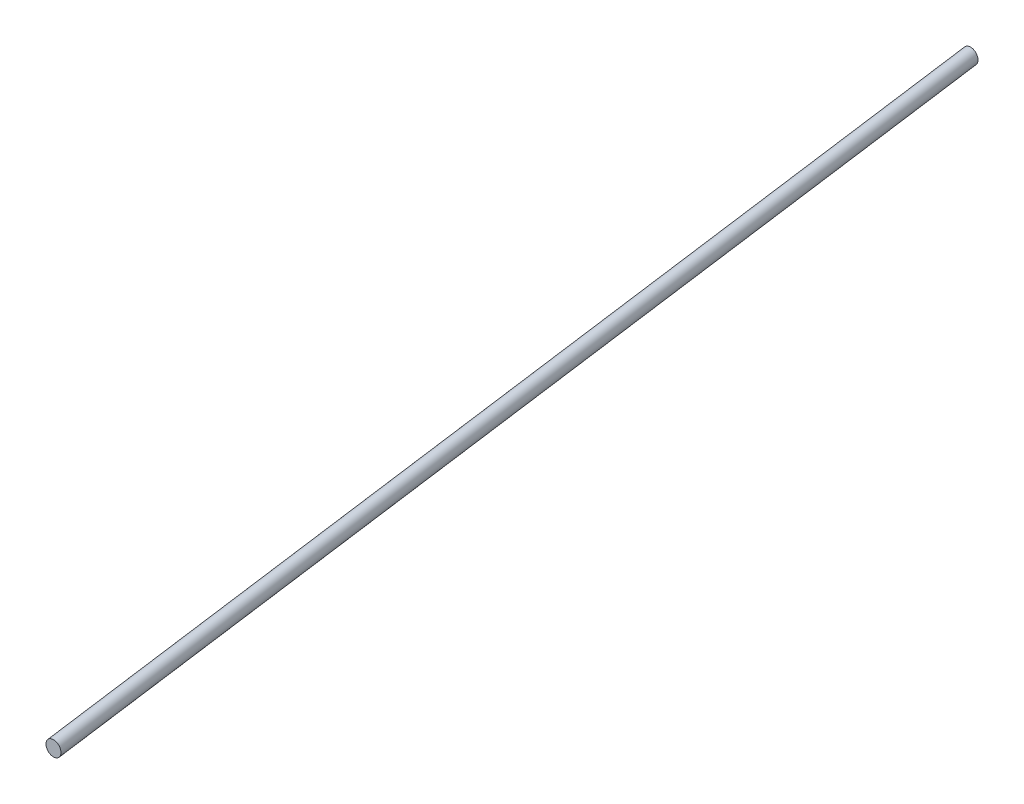
SolidWorks part; units mm, degrees
material "Hexcel AS4C (3000 丝)"
ref_plane "前视基准面" through (0, 0, 0) normal (0, 0, 1) x (1, 0, 0)
ref_plane "上视基准面" through (0, 0, 0) normal (0, 1, 0) x (1, 0, 0)
ref_plane "右视基准面" through (0, 0, 0) normal (1, 0, 0) x (0, 0, -1)
curve "曲线1"
  spline degree 3 poles (186.5, 0.1118, 0) (186.1892, 0.1855, 0) (185.5675, 0.3328, 0) (184.635, 0.5537, 0) (183.7026, 0.7744, 0) (182.7701, 0.9948, 0) (181.8376, 1.2145, 0) (180.9051, 1.4337, 0) (179.9726, 1.652, 0) (178.7297, 1.9419, 0) (177.1757, 2.3014, 0) (175.3109, 2.728, 0) (173.4457, 3.1494, 0) (171.5809, 3.5657, 0) (169.7157, 3.9772, 0) (167.8508, 4.3838, 0) (165.9856, 4.7859, 0) (164.1208, 5.1833, 0) (162.2556, 5.576, 0) (160.3908, 5.9638, 0) (158.5257, 6.3468, 0) (156.6608, 6.7247, 0) (154.7957, 7.0976, 0) (152.9308, 7.4653, 0) (151.0657, 7.8278, 0) (149.2008, 8.185, 0) (147.3357, 8.5369, 0) (145.4708, 8.8834, 0) (143.6056, 9.2245, 0) (141.7408, 9.5601, 0) (139.8756, 9.8903, 0) (138.0108, 10.2149, 0) (136.1456, 10.5341, 0) (134.2808, 10.8476, 0) (132.4156, 11.1557, 0) (130.5507, 11.4581, 0) (128.6856, 11.7549, 0) (126.8208, 12.0459, 0) (124.9556, 12.3308, 0) (123.0908, 12.6092, 0) (121.2257, 12.8811, 0) (119.3608, 13.146, 0) (117.4957, 13.4038, 0) (115.6308, 13.654, 0) (113.7657, 13.8966, 0) (111.9008, 14.1311, 0) (110.0357, 14.3574, 0) (108.1708, 14.5754, 0) (106.3056, 14.785, 0) (104.4407, 14.9862, 0) (102.5756, 15.1791, 0) (100.7107, 15.3636, 0) (98.8455, 15.5397, 0) (96.9806, 15.7073, 0) (95.1155, 15.8666, 0) (93.2506, 16.0175, 0) (91.3854, 16.1599, 0) (89.5205, 16.2936, 0) (87.6554, 16.4183, 0) (85.7905, 16.5335, 0) (83.9254, 16.6389, 0) (82.0604, 16.734, 0) (80.1953, 16.8187, 0) (78.3303, 16.8924, 0) (76.4652, 16.9548, 0) (74.6002, 17.0055, 0) (72.7351, 17.0439, 0) (70.8701, 17.0706, 0) (69.005, 17.0858, 0) (67.14, 17.0901, 0) (65.275, 17.0839, 0) (63.4099, 17.0678, 0) (61.5449, 17.0422, 0) (59.6799, 17.0076, 0) (57.8149, 16.9643, 0) (55.9498, 16.9131, 0) (54.0848, 16.8547, 0) (52.2196, 16.7871, 0) (50.3546, 16.7086, 0) (48.4893, 16.6167, 0) (46.6243, 16.5092, 0) (44.7588, 16.3837, 0) (42.8937, 16.238, 0) (41.028, 16.0697, 0) (39.163, 15.8765, 0) (37.2969, 15.6558, 0) (35.4322, 15.405, 0) (33.5661, 15.1238, 0) (31.7016, 14.8124, 0) (29.8355, 14.4709, 0) (27.971, 14.1006, 0) (26.1044, 13.6997, 0) (24.2398, 13.2683, 0) (22.3723, 12.8019, 0) (20.5078, 12.299, 0) (18.6397, 11.7536, 0) (16.7761, 11.1641, 0) (14.9067, 10.5272, 0) (13.0406, 9.8463, 0) (11.4871, 9.2257, 0) (10.251, 8.6897, 0) (9.3149, 8.2577, 0) (8.3827, 7.7965, 0) (7.4442, 7.2957, 0) (6.5109, 6.7553, 0) (5.5667, 6.1517, 0) (4.6345, 5.4819, 0) (3.7611, 4.7729, 0) (2.9674, 4.0489, 0) (2.3522, 3.4464, 0) (1.8596, 2.9514, 0) (1.4788, 2.552, 0) (1.1014, 2.1276, 0) (0.7887, 1.7312, 0) (0.5474, 1.381, 0) (0.3916, 1.1217, 0) (0.2725, 0.8921, 0) (0.1949, 0.7195, 0) (0.136, 0.5671, 0) (0.0831, 0.4095, 0) (0.0327, 0.2211, 0) (-0.0162, -0.071, 0) (-0.0149, -0.4421, 0) (0.0563, -0.7734, 0) (0.1356, -0.9912, 0) (0.1948, -1.1301, 0) (0.2723, -1.2864, 0) (0.3907, -1.4912, 0) (0.546, -1.7187, 0) (0.7851, -2.0147, 0) (1.0965, -2.3364, 0) (1.4716, -2.656, 0) (1.8524, -2.9339, 0) (2.3365, -3.2337, 0) (2.9612, -3.5284, 0) (3.7741, -3.807, 0) (4.6559, -4.0277, 0) (5.5923, -4.2156, 0) (6.5261, -4.402, 0) (7.4574, -4.5763, 0) (8.3903, -4.7294, 0) (9.3228, -4.8608, 0) (10.2562, -4.9705, 0) (11.4987, -5.092, 0) (13.0535, -5.2066, 0) (14.9192, -5.3092, 0) (16.7846, -5.4024, 0) (18.6495, -5.482, 0) (20.5147, -5.5442, 0) (22.3797, -5.5905, 0) (24.2449, -5.6228, 0) (26.1099, -5.6419, 0) (27.975, -5.6487, 0) (29.84, -5.6442, 0) (31.7051, -5.6295, 0) (33.5701, -5.6055, 0) (35.4351, -5.5733, 0) (37.3001, -5.5337, 0) (39.1651, -5.4878, 0) (41.0301, -5.4363, 0) (42.8951, -5.3798, 0) (44.7601, -5.3192, 0) (46.6251, -5.2551, 0) (48.4901, -5.1881, 0) (50.355, -5.1191, 0) (52.22, -5.0486, 0) (54.085, -4.9774, 0) (55.95, -4.9063, 0) (57.815, -4.8359, 0) (59.68, -4.7662, 0) (61.545, -4.6971, 0) (63.41, -4.6284, 0) (65.275, -4.5602, 0) (67.14, -4.4922, 0) (69.005, -4.4244, 0) (70.87, -4.3567, 0) (72.735, -4.2891, 0) (74.6, -4.2213, 0) (76.465, -4.1533, 0) (78.33, -4.0852, 0) (80.195, -4.0168, 0) (82.06, -3.9484, 0) (83.925, -3.8798, 0) (85.79, -3.8112, 0) (87.655, -3.7425, 0) (89.52, -3.6738, 0) (91.385, -3.6051, 0) (93.25, -3.5364, 0) (95.115, -3.4678, 0) (96.98, -3.3992, 0) (98.845, -3.3306, 0) (100.71, -3.2621, 0) (102.575, -3.1937, 0) (104.44, -3.1252, 0) (106.305, -3.0568, 0) (108.17, -2.9883, 0) (110.035, -2.9199, 0) (111.9, -2.8515, 0) (113.765, -2.783, 0) (115.63, -2.7145, 0) (117.495, -2.6461, 0) (119.36, -2.5776, 0) (121.225, -2.5091, 0) (123.09, -2.4406, 0) (124.955, -2.3721, 0) (126.82, -2.3035, 0) (128.685, -2.2351, 0) (130.55, -2.1665, 0) (132.415, -2.0981, 0) (134.28, -2.0295, 0) (136.145, -1.9611, 0) (138.01, -1.8926, 0) (139.875, -1.8241, 0) (141.74, -1.7556, 0) (143.605, -1.6871, 0) (145.47, -1.6186, 0) (147.335, -1.5501, 0) (149.2, -1.4816, 0) (151.065, -1.4131, 0) (152.93, -1.3446, 0) (154.795, -1.2761, 0) (156.66, -1.2076, 0) (158.525, -1.1392, 0) (160.39, -1.0707, 0) (162.255, -1.0022, 0) (164.12, -0.9337, 0) (165.985, -0.8652, 0) (167.85, -0.7967, 0) (169.715, -0.7282, 0) (171.58, -0.6597, 0) (173.445, -0.5912, 0) (175.31, -0.5227, 0) (177.175, -0.4542, 0) (178.7292, -0.3972, 0) (179.9725, -0.3515, 0) (180.905, -0.3173, 0) (181.8375, -0.283, 0) (182.77, -0.2488, 0) (183.7025, -0.2145, 0) (184.635, -0.1803, 0) (185.5675, -0.146, 0) (186.1892, -0.1232, 0) (186.5, -0.1118, 0) knots 0 0 0 0 0.002514 0.005028 0.007541 0.010055 0.012567 0.01508 0.017592 0.020104 0.025124 0.030144 0.035158 0.040172 0.04518 0.050189 0.055192 0.060195 0.065193 0.070191 0.075184 0.080177 0.085164 0.090152 0.095134 0.100117 0.105094 0.110071 0.115043 0.120015 0.124982 0.129949 0.134911 0.139873 0.14483 0.149787 0.154739 0.159692 0.164639 0.169587 0.174529 0.179472 0.184409 0.189346 0.194278 0.19921 0.204137 0.209064 0.213985 0.218907 0.223824 0.228741 0.233654 0.238567 0.243476 0.248385 0.25329 0.258196 0.263098 0.268 0.2729 0.277799 0.282695 0.287592 0.292486 0.29738 0.302273 0.307166 0.312058 0.316951 0.321843 0.326735 0.331628 0.33652 0.341414 0.346308 0.351203 0.356098 0.360995 0.365892 0.370794 0.375696 0.380605 0.385515 0.390437 0.39536 0.400301 0.405243 0.410209 0.415176 0.420172 0.425167 0.430199 0.435232 0.440314 0.445396 0.450545 0.455694 0.460935 0.466175 0.468856 0.471537 0.474288 0.477039 0.479906 0.482773 0.485854 0.488934 0.491619 0.494305 0.49571 0.497115 0.498647 0.500178 0.501085 0.501992 0.502556 0.503119 0.50348 0.503841 0.504427 0.505013 0.506168 0.507324 0.507658 0.507992 0.508511 0.50903 0.509853 0.510676 0.512022 0.513369 0.514549 0.515728 0.517845 0.519968 0.522481 0.524993 0.527484 0.529974 0.532448 0.534923 0.537383 0.539844 0.544747 0.54965 0.554547 0.559445 0.564339 0.569233 0.574126 0.579018 0.58391 0.588803 0.593695 0.598587 0.60348 0.608373 0.613267 0.618161 0.623055 0.62795 0.632845 0.63774 0.642636 0.647531 0.652427 0.657322 0.662218 0.667113 0.672009 0.676904 0.6818 0.686695 0.69159 0.696486 0.701381 0.706276 0.711172 0.716067 0.720962 0.725858 0.730753 0.735649 0.740544 0.745439 0.750335 0.75523 0.760126 0.765021 0.769916 0.774812 0.779707 0.784603 0.789498 0.794393 0.799289 0.804184 0.80908 0.813975 0.81887 0.823766 0.828661 0.833557 0.838452 0.843347 0.848243 0.853138 0.858034 0.862929 0.867824 0.87272 0.877615 0.882511 0.887406 0.892301 0.897197 0.902092 0.906987 0.911883 0.916778 0.921674 0.926569 0.931464 0.93636 0.941255 0.946151 0.951046 0.955941 0.960837 0.965732 0.970628 0.975523 0.980418 0.982866 0.985314 0.987762 0.990209 0.992657 0.995105 0.997552 1 1 1 1
sketch "草图1" plane through (0, 0, 0) normal (0, 0, 1) x (1, 0, 0)
  line L0 (186.5, 0.1118) -> (187.3165, -0.0818)
  line L1 (186.5, -0.1118) -> (187.3165, -0.0818)
  spline S0 degree 3 poles (1071.8943, 1773.6481) (478.7543, -73.3687) (332.3255, -34.4387) (184.635, 0.5537) (183.7026, 0.7744) (182.7701, 0.9948) (181.8376, 1.2145) (180.9051, 1.4337) (179.9726, 1.652) (178.7297, 1.9419) (177.1757, 2.3014) (175.3109, 2.728) (173.4457, 3.1494) (170.9597, 3.7043) (167.8519, 4.3859) (164.1219, 5.1854) (159.7716, 6.0959) (156.0406, 6.8521) (152.9308, 7.4653) (151.0657, 7.8278) (149.2008, 8.185) (147.3357, 8.5369) (145.4708, 8.8834) (143.6056, 9.2245) (141.7408, 9.5601) (139.2547, 10.0002) (136.7681, 10.4294) (134.2808, 10.8476) (132.4156, 11.1557) (130.5507, 11.4581) (128.6856, 11.7549) (126.8208, 12.0459) (124.9556, 12.3308) (123.0908, 12.6092) (121.2257, 12.8811) (119.3608, 13.146) (117.4957, 13.4038) (115.0097, 13.7374) (112.523, 14.0557) (109.4148, 14.4328) (106.9281, 14.7178) (104.4407, 14.9862) (102.5756, 15.1791) (100.7107, 15.3636) (98.8455, 15.5397) (96.3593, 15.7632) (93.2513, 16.0216) (90.1425, 16.252) (87.6554, 16.4183) (85.7905, 16.5335) (83.9254, 16.6389) (82.0604, 16.734) (80.1953, 16.8187) (78.3303, 16.8924) (76.4652, 16.9548) (73.9787, 17.0223) (71.4919, 17.0655) (69.005, 17.0858) (67.14, 17.0901) (65.275, 17.0839) (63.4099, 17.0678) (61.5449, 17.0422) (59.6799, 17.0076) (57.8149, 16.9643) (55.9498, 16.9131) (54.0848, 16.8547) (52.2196, 16.7871) (50.3546, 16.7086) (48.4893, 16.6167) (46.6243, 16.5092) (44.7588, 16.3837) (42.8937, 16.238) (41.028, 16.0697) (39.163, 15.8765) (37.2969, 15.6558) (35.4322, 15.405) (33.5661, 15.1238) (31.7016, 14.8124) (29.8355, 14.4709) (27.971, 14.1006) (26.1044, 13.6997) (24.2398, 13.2683) (22.3723, 12.8019) (20.5078, 12.299) (18.6397, 11.7536) (16.7761, 11.1641) (14.9067, 10.5272) (13.0406, 9.8463) (11.4871, 9.2257) (10.251, 8.6897) (9.3149, 8.2577) (8.3827, 7.7965) (7.4442, 7.2957) (6.5109, 6.7553) (5.5667, 6.1517) (4.6345, 5.4819) (3.7611, 4.7729) (2.9674, 4.0489) (2.3522, 3.4464) (1.8596, 2.9514) (1.4788, 2.552) (1.1014, 2.1276) (0.7887, 1.7312) (0.5474, 1.381) (0.3916, 1.1217) (0.2725, 0.8921) (0.1949, 0.7195) (0.136, 0.5671) (0.0831, 0.4095) (0.0327, 0.2211) (-0.0162, -0.071) (-0.0149, -0.4421) (0.0563, -0.7734) (0.1356, -0.9912) (0.1948, -1.1301) (0.2723, -1.2864) (0.3907, -1.4912) (0.546, -1.7187) (0.7851, -2.0147) (1.0965, -2.3364) (1.4716, -2.656) (1.8524, -2.9339) (2.3365, -3.2337) (2.9612, -3.5284) (3.7741, -3.807) (4.6559, -4.0277) (5.5923, -4.2156) (6.5261, -4.402) (7.4574, -4.5763) (8.3903, -4.7294) (9.3228, -4.8608) (10.2562, -4.9705) (11.4987, -5.092) (13.0535, -5.2066) (14.9192, -5.3092) (16.7846, -5.4024) (18.6495, -5.482) (20.5147, -5.5442) (22.3797, -5.5905) (24.8665, -5.6336) (27.3533, -5.6502) (29.84, -5.6442) (32.3268, -5.6246) (34.8135, -5.5864) (37.3001, -5.5337) (39.1651, -5.4878) (42.2737, -5.4019) (45.3819, -5.2997) (49.1118, -5.1658) (51.5984, -5.0723) (54.085, -4.9774) (57.1933, -4.8589) (61.5449, -4.6964) (66.5183, -4.5147) (70.2483, -4.3793) (73.3567, -4.2665) (75.8433, -4.176) (78.33, -4.0852) (80.195, -4.0168) (82.06, -3.9484) (83.925, -3.8798) (85.79, -3.8112) (87.655, -3.7425) (89.52, -3.6738) (91.385, -3.6051) (93.25, -3.5364) (95.7367, -3.4449) (98.2233, -3.3535) (100.71, -3.2621) (102.575, -3.1937) (104.44, -3.1252) (106.305, -3.0568) (108.7917, -2.9655) (111.2783, -2.8743) (113.765, -2.783) (116.8733, -2.6689) (119.9817, -2.5547) (123.09, -2.4406) (124.955, -2.3721) (126.82, -2.3035) (129.3067, -2.2122) (131.7933, -2.1209) (134.28, -2.0295) (136.145, -1.9611) (138.01, -1.8926) (140.4967, -1.8012) (142.9833, -1.7099) (145.47, -1.6186) (147.335, -1.5501) (149.8217, -1.4588) (152.3083, -1.3675) (154.795, -1.2761) (156.66, -1.2076) (158.525, -1.1392) (160.39, -1.0707) (162.255, -1.0022) (164.12, -0.9337) (166.6067, -0.8424) (169.0933, -0.751) (171.58, -0.6597) (174.0667, -0.5684) (176.5533, -0.4771) (179.04, -0.3857) (180.5942, -0.3287) (182.1483, -0.2716) (183.3917, -0.2259) (184.635, -0.1803) (849.3977, 24.2359) (1513.8472, 48.7041) (2182.9555, -62.1484) knots -1.186859 -1.186859 -1.186859 -1.186859 0.002514 0.005028 0.007541 0.010055 0.012567 0.01508 0.017592 0.020104 0.025124 0.030144 0.035158 0.040172 0.050189 0.060195 0.070191 0.085164 0.090152 0.095134 0.100117 0.105094 0.110071 0.115043 0.120015 0.124982 0.134911 0.139873 0.14483 0.149787 0.154739 0.159692 0.164639 0.169587 0.174529 0.179472 0.184409 0.189346 0.19921 0.204137 0.213985 0.218907 0.223824 0.228741 0.233654 0.238567 0.248385 0.258196 0.263098 0.268 0.2729 0.277799 0.282695 0.287592 0.292486 0.29738 0.307166 0.312058 0.316951 0.321843 0.326735 0.331628 0.33652 0.341414 0.346308 0.351203 0.356098 0.360995 0.365892 0.370794 0.375696 0.380605 0.385515 0.390437 0.39536 0.400301 0.405243 0.410209 0.415176 0.420172 0.425167 0.430199 0.435232 0.440314 0.445396 0.450545 0.455694 0.460935 0.466175 0.468856 0.471537 0.474288 0.477039 0.479906 0.482773 0.485854 0.488934 0.491619 0.494305 0.49571 0.497115 0.498647 0.500178 0.501085 0.501992 0.502556 0.503119 0.50348 0.503841 0.504427 0.505013 0.506168 0.507324 0.507658 0.507992 0.508511 0.50903 0.509853 0.510676 0.512022 0.513369 0.514549 0.515728 0.517845 0.519968 0.522481 0.524993 0.527484 0.529974 0.532448 0.534923 0.537383 0.539844 0.544747 0.54965 0.554547 0.559445 0.564339 0.569233 0.574126 0.58391 0.588803 0.593695 0.60348 0.608373 0.613267 0.618161 0.632845 0.63774 0.647531 0.652427 0.657322 0.672009 0.686695 0.696486 0.701381 0.711172 0.716067 0.720962 0.725858 0.730753 0.735649 0.740544 0.745439 0.750335 0.75523 0.760126 0.769916 0.774812 0.779707 0.784603 0.789498 0.794393 0.804184 0.80908 0.813975 0.828661 0.833557 0.838452 0.843347 0.848243 0.858034 0.862929 0.867824 0.87272 0.877615 0.887406 0.892301 0.897197 0.902092 0.911883 0.916778 0.921674 0.926569 0.931464 0.93636 0.941255 0.946151 0.955941 0.960837 0.965732 0.975523 0.980418 0.985314 0.987762 0.992657 0.995105 0.997552 6.227418 6.227418 6.227418 6.227418 only from (186.5, 0.1118) to (186.5, -0.1118) construction
  spline S1 degree 3 poles (186.5, 0.1118) (185.8783, 0.2591) (184.9459, 0.4802) (183.7026, 0.7744) (182.7701, 0.9948) (181.8376, 1.2145) (180.9051, 1.4337) (179.9726, 1.652) (178.7297, 1.9419) (177.1757, 2.3014) (175.3109, 2.728) (173.4457, 3.1494) (170.9597, 3.7043) (167.8519, 4.3859) (164.1219, 5.1854) (159.7716, 6.0959) (156.0406, 6.8521) (152.9308, 7.4653) (151.0657, 7.8278) (149.2008, 8.185) (147.3357, 8.5369) (145.4708, 8.8834) (143.6056, 9.2245) (141.7408, 9.5601) (139.2547, 10.0002) (136.7681, 10.4294) (134.2808, 10.8476) (132.4156, 11.1557) (130.5507, 11.4581) (128.6856, 11.7549) (126.8208, 12.0459) (124.9556, 12.3308) (123.0908, 12.6092) (121.2257, 12.8811) (119.3608, 13.146) (117.4957, 13.4038) (115.0097, 13.7374) (112.523, 14.0557) (109.4148, 14.4328) (106.9281, 14.7178) (104.4407, 14.9862) (102.5756, 15.1791) (100.7107, 15.3636) (98.8455, 15.5397) (96.3593, 15.7632) (93.2513, 16.0216) (90.1425, 16.252) (87.6554, 16.4183) (85.7905, 16.5335) (83.9254, 16.6389) (82.0604, 16.734) (80.1953, 16.8187) (78.3303, 16.8924) (76.4652, 16.9548) (73.9787, 17.0223) (71.4919, 17.0655) (69.005, 17.0858) (67.14, 17.0901) (65.275, 17.0839) (63.4099, 17.0678) (61.5449, 17.0422) (59.6799, 17.0076) (57.8149, 16.9643) (55.9498, 16.9131) (54.0848, 16.8547) (52.2196, 16.7871) (50.3546, 16.7086) (48.4893, 16.6167) (46.6243, 16.5092) (44.7588, 16.3837) (42.8937, 16.238) (41.028, 16.0697) (39.163, 15.8765) (37.2969, 15.6558) (35.4322, 15.405) (33.5661, 15.1238) (31.7016, 14.8124) (29.8355, 14.4709) (27.971, 14.1006) (26.1044, 13.6997) (24.2398, 13.2683) (22.3723, 12.8019) (20.5078, 12.299) (18.6397, 11.7536) (16.7761, 11.1641) (14.9067, 10.5272) (13.0406, 9.8463) (11.4871, 9.2257) (10.251, 8.6897) (9.3149, 8.2577) (8.3827, 7.7965) (7.4442, 7.2957) (6.5109, 6.7553) (5.5667, 6.1517) (4.6345, 5.4819) (3.7611, 4.7729) (2.9674, 4.0489) (2.3522, 3.4464) (1.8596, 2.9514) (1.4788, 2.552) (1.1014, 2.1276) (0.7887, 1.7312) (0.5474, 1.381) (0.3916, 1.1217) (0.2725, 0.8921) (0.1949, 0.7195) (0.136, 0.5671) (0.0831, 0.4095) (0.0327, 0.2211) (-0.0162, -0.071) (-0.0149, -0.4421) (0.0563, -0.7734) (0.1356, -0.9912) (0.1948, -1.1301) (0.2723, -1.2864) (0.3907, -1.4912) (0.546, -1.7187) (0.7851, -2.0147) (1.0965, -2.3364) (1.4716, -2.656) (1.8524, -2.9339) (2.3365, -3.2337) (2.9612, -3.5284) (3.7741, -3.807) (4.6559, -4.0277) (5.5923, -4.2156) (6.5261, -4.402) (7.4574, -4.5763) (8.3903, -4.7294) (9.3228, -4.8608) (10.2562, -4.9705) (11.4987, -5.092) (13.0535, -5.2066) (14.9192, -5.3092) (16.7846, -5.4024) (18.6495, -5.482) (20.5147, -5.5442) (22.3797, -5.5905) (24.8665, -5.6336) (27.3533, -5.6502) (29.84, -5.6442) (32.3268, -5.6246) (34.8135, -5.5864) (37.3001, -5.5337) (39.1651, -5.4878) (42.2737, -5.4019) (45.3819, -5.2997) (49.1118, -5.1658) (51.5984, -5.0723) (54.085, -4.9774) (57.1933, -4.8589) (61.5449, -4.6964) (66.5183, -4.5147) (70.2483, -4.3793) (73.3567, -4.2665) (75.8433, -4.176) (78.33, -4.0852) (80.195, -4.0168) (82.06, -3.9484) (83.925, -3.8798) (85.79, -3.8112) (87.655, -3.7425) (89.52, -3.6738) (91.385, -3.6051) (93.25, -3.5364) (95.7367, -3.4449) (98.2233, -3.3535) (100.71, -3.2621) (102.575, -3.1937) (104.44, -3.1252) (106.305, -3.0568) (108.7917, -2.9655) (111.2783, -2.8743) (113.765, -2.783) (116.8733, -2.6689) (119.9817, -2.5547) (123.09, -2.4406) (124.955, -2.3721) (126.82, -2.3035) (129.3067, -2.2122) (131.7933, -2.1209) (134.28, -2.0295) (136.145, -1.9611) (138.01, -1.8926) (140.4967, -1.8012) (142.9833, -1.7099) (145.47, -1.6186) (147.335, -1.5501) (149.8217, -1.4588) (152.3083, -1.3675) (154.795, -1.2761) (156.66, -1.2076) (158.525, -1.1392) (160.39, -1.0707) (162.255, -1.0022) (164.12, -0.9337) (166.6067, -0.8424) (169.0933, -0.751) (171.58, -0.6597) (174.0667, -0.5684) (176.5533, -0.4771) (179.04, -0.3857) (180.5942, -0.3287) (182.1483, -0.2716) (184.0133, -0.2031) (185.5675, -0.146) (186.5, -0.1118) knots 0 0 0 0 0.005028 0.007541 0.010055 0.012567 0.01508 0.017592 0.020104 0.025124 0.030144 0.035158 0.040172 0.050189 0.060195 0.070191 0.085164 0.090152 0.095134 0.100117 0.105094 0.110071 0.115043 0.120015 0.124982 0.134911 0.139873 0.14483 0.149787 0.154739 0.159692 0.164639 0.169587 0.174529 0.179472 0.184409 0.189346 0.19921 0.204137 0.213985 0.218907 0.223824 0.228741 0.233654 0.238567 0.248385 0.258196 0.263098 0.268 0.2729 0.277799 0.282695 0.287592 0.292486 0.29738 0.307166 0.312058 0.316951 0.321843 0.326735 0.331628 0.33652 0.341414 0.346308 0.351203 0.356098 0.360995 0.365892 0.370794 0.375696 0.380605 0.385515 0.390437 0.39536 0.400301 0.405243 0.410209 0.415176 0.420172 0.425167 0.430199 0.435232 0.440314 0.445396 0.450545 0.455694 0.460935 0.466175 0.468856 0.471537 0.474288 0.477039 0.479906 0.482773 0.485854 0.488934 0.491619 0.494305 0.49571 0.497115 0.498647 0.500178 0.501085 0.501992 0.502556 0.503119 0.50348 0.503841 0.504427 0.505013 0.506168 0.507324 0.507658 0.507992 0.508511 0.50903 0.509853 0.510676 0.512022 0.513369 0.514549 0.515728 0.517845 0.519968 0.522481 0.524993 0.527484 0.529974 0.532448 0.534923 0.537383 0.539844 0.544747 0.54965 0.554547 0.559445 0.564339 0.569233 0.574126 0.58391 0.588803 0.593695 0.60348 0.608373 0.613267 0.618161 0.632845 0.63774 0.647531 0.652427 0.657322 0.672009 0.686695 0.696486 0.701381 0.711172 0.716067 0.720962 0.725858 0.730753 0.735649 0.740544 0.745439 0.750335 0.75523 0.760126 0.769916 0.774812 0.779707 0.784603 0.789498 0.794393 0.804184 0.80908 0.813975 0.828661 0.833557 0.838452 0.843347 0.848243 0.858034 0.862929 0.867824 0.87272 0.877615 0.887406 0.892301 0.897197 0.902092 0.911883 0.916778 0.921674 0.926569 0.931464 0.93636 0.941255 0.946151 0.955941 0.960837 0.965732 0.975523 0.980418 0.985314 0.987762 0.992657 1 1 1 1
curve "组合曲线1"
ref_plane "基准面4" through (0, 0, 519) normal (0, 0, 1) x (1, 0, 0)
sketch "草图2" plane through (0, 0, 519) normal (0, 0, 1) x (1, 0, 0)
  line L2 (187.3165, -0.0818) -> (186.8021, 0.0402)
  line L3 (186.8021, -0.1007) -> (187.3165, -0.0818)
  spline S1 degree 3 poles (186.8021, 0.0402) (186.2146, 0.1794) (185.4313, 0.3651) (184.4521, 0.5965) (183.8645, 0.735) (183.2771, 0.873) (182.6895, 1.0106) (181.9064, 1.1932) (180.9273, 1.4197) (179.7524, 1.6885) (178.5773, 1.954) (177.011, 2.3036) (175.0529, 2.733) (172.7029, 3.2368) (169.962, 3.8104) (167.6113, 4.2869) (165.652, 4.6732) (164.0857, 4.9777) (162.519, 5.2755) (160.9518, 5.5667) (159.7767, 5.7816) (158.6017, 5.993) (157.0354, 6.2703) (155.4687, 6.5408) (153.9016, 6.8042) (152.7265, 6.9983) (151.5515, 7.1888) (150.3764, 7.3759) (149.2015, 7.5592) (148.0263, 7.7387) (146.8514, 7.9141) (145.2851, 8.1425) (143.7184, 8.3621) (141.7599, 8.6249) (140.1932, 8.8254) (138.2349, 9.063) (136.6682, 9.2426) (135.101, 9.4117) (133.9259, 9.5333) (132.7509, 9.6495) (131.5758, 9.7604) (130.0094, 9.9013) (128.0512, 10.0641) (126.0925, 10.2092) (124.5255, 10.314) (123.3505, 10.3866) (122.1754, 10.453) (121.0004, 10.5129) (119.8253, 10.5663) (118.6503, 10.6127) (117.4752, 10.652) (115.9086, 10.6946) (114.3418, 10.7218) (112.775, 10.7346) (111.5999, 10.7373) (110.4248, 10.7334) (109.2498, 10.7232) (108.0747, 10.7071) (106.8997, 10.6853) (105.7246, 10.658) (104.5496, 10.6257) (103.3745, 10.5889) (102.1994, 10.5464) (101.0243, 10.4969) (99.8491, 10.439) (98.6741, 10.3713) (97.4987, 10.2922) (96.3237, 10.2004) (95.1481, 10.0944) (93.9731, 9.9727) (92.7974, 9.8336) (91.6225, 9.6756) (90.4468, 9.4984) (89.2721, 9.3022) (88.0964, 9.0871) (86.9217, 8.8538) (85.7456, 8.6012) (84.5708, 8.3294) (83.3943, 8.0355) (82.2195, 7.7187) (81.0425, 7.375) (79.8683, 7.0036) (78.6906, 6.6023) (77.5148, 6.1733) (76.5361, 5.7823) (75.7573, 5.4447) (75.1675, 5.1725) (74.5801, 4.8819) (73.9888, 4.5664) (73.4008, 4.2259) (72.806, 3.8456) (72.2186, 3.4236) (71.6683, 2.9769) (71.1683, 2.5208) (70.7807, 2.1411) (70.4703, 1.8292) (70.2304, 1.5776) (69.9926, 1.3102) (69.7956, 1.0605) (69.6436, 0.8398) (69.5454, 0.6765) (69.4703, 0.5318) (69.4215, 0.4231) (69.3844, 0.327) (69.3511, 0.2278) (69.3193, 0.1091) (69.2885, -0.075) (69.2893, -0.3088) (69.3342, -0.5175) (69.3841, -0.6548) (69.4214, -0.7423) (69.4702, -0.8408) (69.5448, -0.9698) (69.6427, -1.1131) (69.7933, -1.2996) (69.9895, -1.5023) (70.2258, -1.7037) (70.4657, -1.8787) (70.7708, -2.0676) (71.1644, -2.2533) (71.6765, -2.4288) (72.2321, -2.5679) (72.8221, -2.6862) (73.4104, -2.8037) (73.9972, -2.9135) (74.585, -3.01) (75.1724, -3.0928) (75.7605, -3.1619) (76.5434, -3.2385) (77.5229, -3.3106) (78.6984, -3.3753) (79.8737, -3.434) (81.0487, -3.4842) (82.2238, -3.5233) (83.3989, -3.5525) (84.9657, -3.5796) (86.5325, -3.5901) (88.0992, -3.5863) (89.666, -3.574) (91.2328, -3.55) (92.7994, -3.5167) (93.9744, -3.4878) (95.933, -3.4337) (97.8913, -3.3693) (100.2413, -3.2849) (102.1997, -3.2113) (104.9413, -3.1062) (108.0747, -2.9892) (111.2082, -2.8747) (113.5583, -2.7894) (115.5167, -2.7184) (117.0834, -2.6614) (118.6501, -2.6041) (119.8251, -2.561) (121.0002, -2.5179) (122.1752, -2.4747) (123.7419, -2.4171) (125.3086, -2.3593) (126.8753, -2.3016) (128.0504, -2.2583) (129.6171, -2.2007) (131.1838, -2.1431) (132.7505, -2.0856) (133.9255, -2.0424) (135.1006, -1.9993) (136.2756, -1.9562) (137.8423, -1.8987) (139.409, -1.8412) (140.9757, -1.7837) (142.9341, -1.7118) (144.8925, -1.6398) (147.2426, -1.5536) (148.8093, -1.496) (150.7677, -1.4241) (152.3344, -1.3665) (153.9011, -1.309) (155.0761, -1.2658) (156.2512, -1.2227) (157.8179, -1.1651) (159.3846, -1.1076) (160.9513, -1.05) (162.1264, -1.0069) (163.6931, -0.9494) (165.2598, -0.8918) (166.8265, -0.8343) (168.7849, -0.7623) (170.7433, -0.6904) (172.7017, -0.6185) (174.2684, -0.561) (175.8351, -0.5034) (177.4018, -0.4459) (178.9685, -0.3884) (180.5352, -0.3308) (182.1019, -0.2733) (183.0811, -0.2373) (184.0603, -0.2014) (185.2354, -0.1582) (186.2145, -0.1223) (186.8021, -0.1007) knots 0 0 0 0 0.007541 0.010055 0.012567 0.01508 0.017592 0.020104 0.025124 0.030144 0.035158 0.040172 0.050189 0.060195 0.070191 0.085164 0.090152 0.095134 0.105094 0.110071 0.115043 0.120015 0.124982 0.134911 0.139873 0.14483 0.149787 0.154739 0.159692 0.164639 0.169587 0.174529 0.184409 0.189346 0.19921 0.204137 0.213985 0.218907 0.223824 0.228741 0.233654 0.238567 0.248385 0.258196 0.263098 0.268 0.2729 0.277799 0.282695 0.287592 0.292486 0.29738 0.307166 0.312058 0.316951 0.321843 0.326735 0.331628 0.33652 0.341414 0.346308 0.351203 0.356098 0.360995 0.365892 0.370794 0.375696 0.380605 0.385515 0.390437 0.39536 0.400301 0.405243 0.410209 0.415176 0.420172 0.425167 0.430199 0.435232 0.440314 0.445396 0.450545 0.455694 0.460935 0.466175 0.468856 0.471537 0.474288 0.477039 0.479906 0.482773 0.485854 0.488934 0.491619 0.494305 0.49571 0.497115 0.498647 0.500178 0.501085 0.501992 0.502556 0.503119 0.50348 0.503841 0.504427 0.505013 0.506168 0.507324 0.507658 0.507992 0.508511 0.50903 0.509853 0.510676 0.512022 0.513369 0.514549 0.515728 0.517845 0.519968 0.522481 0.524993 0.527484 0.529974 0.532448 0.534923 0.537383 0.539844 0.544747 0.54965 0.554547 0.559445 0.564339 0.569233 0.574126 0.58391 0.588803 0.593695 0.60348 0.608373 0.613267 0.618161 0.632845 0.63774 0.647531 0.657322 0.672009 0.686695 0.696486 0.701381 0.711172 0.716067 0.720962 0.725858 0.730753 0.735649 0.745439 0.750335 0.75523 0.760126 0.769916 0.774812 0.779707 0.784603 0.789498 0.794393 0.804184 0.80908 0.813975 0.828661 0.833557 0.843347 0.848243 0.858034 0.862929 0.867824 0.87272 0.877615 0.887406 0.892301 0.897197 0.902092 0.911883 0.916778 0.921674 0.93636 0.941255 0.946151 0.955941 0.960837 0.965732 0.975523 0.980418 0.985314 0.987762 0.992657 1 1 1 1
curve "组合曲线2"
sketch3d "3D草图1"
  line L0 (-0.0101, -0.1358, 0) -> (69.2923, -0.1173, 519)
  line L1 (187.3165, -0.0818, 0) -> (187.3165, -0.0818, 519)
  line L2 (187.3165, -0.0818, 0) -> (186.5, 0.1118, 0) construction
  line L3 (186.5, -0.1118, 0) -> (187.3165, -0.0818, 0) construction
  line L4 (187.3165, -0.0818, 519) -> (186.8021, 0.0402, 519) construction
  line L5 (186.8021, -0.1007, 519) -> (187.3165, -0.0818, 519) construction
  spline S0 degree 3 poles (186.5, 0.1118, 0) (185.8783, 0.2591, 0) (184.9459, 0.4802, 0) (183.7026, 0.7744, 0) (182.7701, 0.9948, 0) (181.8376, 1.2145, 0) (180.9051, 1.4337, 0) (179.9726, 1.652, 0) (178.7297, 1.9419, 0) (177.1757, 2.3014, 0) (175.3109, 2.728, 0) (173.4457, 3.1494, 0) (170.9597, 3.7043, 0) (167.8519, 4.3859, 0) (164.1219, 5.1854, 0) (159.7716, 6.0959, 0) (156.0406, 6.8521, 0) (152.9308, 7.4653, 0) (151.0657, 7.8278, 0) (149.2008, 8.185, 0) (147.3357, 8.5369, 0) (145.4708, 8.8834, 0) (143.6056, 9.2245, 0) (141.7408, 9.5601, 0) (139.2547, 10.0002, 0) (136.7681, 10.4294, 0) (134.2808, 10.8476, 0) (132.4156, 11.1557, 0) (130.5507, 11.4581, 0) (128.6856, 11.7549, 0) (126.8208, 12.0459, 0) (124.9556, 12.3308, 0) (123.0908, 12.6092, 0) (121.2257, 12.8811, 0) (119.3608, 13.146, 0) (117.4957, 13.4038, 0) (115.0097, 13.7374, 0) (112.523, 14.0557, 0) (109.4148, 14.4328, 0) (106.9281, 14.7178, 0) (104.4407, 14.9862, 0) (102.5756, 15.1791, 0) (100.7107, 15.3636, 0) (98.8455, 15.5397, 0) (96.3593, 15.7632, 0) (93.2513, 16.0216, 0) (90.1425, 16.252, 0) (87.6554, 16.4183, 0) (85.7905, 16.5335, 0) (83.9254, 16.6389, 0) (82.0604, 16.734, 0) (80.1953, 16.8187, 0) (78.3303, 16.8924, 0) (76.4652, 16.9548, 0) (73.9787, 17.0223, 0) (71.4919, 17.0655, 0) (69.005, 17.0858, 0) (67.14, 17.0901, 0) (65.275, 17.0839, 0) (63.4099, 17.0678, 0) (61.5449, 17.0422, 0) (59.6799, 17.0076, 0) (57.8149, 16.9643, 0) (55.9498, 16.9131, 0) (54.0848, 16.8547, 0) (52.2196, 16.7871, 0) (50.3546, 16.7086, 0) (48.4893, 16.6167, 0) (46.6243, 16.5092, 0) (44.7588, 16.3837, 0) (42.8937, 16.238, 0) (41.028, 16.0697, 0) (39.163, 15.8765, 0) (37.2969, 15.6558, 0) (35.4322, 15.405, 0) (33.5661, 15.1238, 0) (31.7016, 14.8124, 0) (29.8355, 14.4709, 0) (27.971, 14.1006, 0) (26.1044, 13.6997, 0) (24.2398, 13.2683, 0) (22.3723, 12.8019, 0) (20.5078, 12.299, 0) (18.6397, 11.7536, 0) (16.7761, 11.1641, 0) (14.9067, 10.5272, 0) (13.0406, 9.8463, 0) (11.4871, 9.2257, 0) (10.251, 8.6897, 0) (9.3149, 8.2577, 0) (8.3827, 7.7965, 0) (7.4442, 7.2957, 0) (6.5109, 6.7553, 0) (5.5667, 6.1517, 0) (4.6345, 5.4819, 0) (3.7611, 4.7729, 0) (2.9674, 4.0489, 0) (2.3522, 3.4464, 0) (1.8596, 2.9514, 0) (1.4788, 2.552, 0) (1.1014, 2.1276, 0) (0.7887, 1.7312, 0) (0.5474, 1.381, 0) (0.3916, 1.1217, 0) (0.2725, 0.8921, 0) (0.1949, 0.7195, 0) (0.136, 0.5671, 0) (0.0831, 0.4095, 0) (0.0327, 0.2211, 0) (-0.0162, -0.071, 0) (-0.0149, -0.4421, 0) (0.0563, -0.7734, 0) (0.1356, -0.9912, 0) (0.1948, -1.1301, 0) (0.2723, -1.2864, 0) (0.3907, -1.4912, 0) (0.546, -1.7187, 0) (0.7851, -2.0147, 0) (1.0965, -2.3364, 0) (1.4716, -2.656, 0) (1.8524, -2.9339, 0) (2.3365, -3.2337, 0) (2.9612, -3.5284, 0) (3.7741, -3.807, 0) (4.6559, -4.0277, 0) (5.5923, -4.2156, 0) (6.5261, -4.402, 0) (7.4574, -4.5763, 0) (8.3903, -4.7294, 0) (9.3228, -4.8608, 0) (10.2562, -4.9705, 0) (11.4987, -5.092, 0) (13.0535, -5.2066, 0) (14.9192, -5.3092, 0) (16.7846, -5.4024, 0) (18.6495, -5.482, 0) (20.5147, -5.5442, 0) (22.3797, -5.5905, 0) (24.8665, -5.6336, 0) (27.3533, -5.6502, 0) (29.84, -5.6442, 0) (32.3268, -5.6246, 0) (34.8135, -5.5864, 0) (37.3001, -5.5337, 0) (39.1651, -5.4878, 0) (42.2737, -5.4019, 0) (45.3819, -5.2997, 0) (49.1118, -5.1658, 0) (51.5984, -5.0723, 0) (54.085, -4.9774, 0) (57.1933, -4.8589, 0) (61.5449, -4.6964, 0) (66.5183, -4.5147, 0) (70.2483, -4.3793, 0) (73.3567, -4.2665, 0) (75.8433, -4.176, 0) (78.33, -4.0852, 0) (80.195, -4.0168, 0) (82.06, -3.9484, 0) (83.925, -3.8798, 0) (85.79, -3.8112, 0) (87.655, -3.7425, 0) (89.52, -3.6738, 0) (91.385, -3.6051, 0) (93.25, -3.5364, 0) (95.7367, -3.4449, 0) (98.2233, -3.3535, 0) (100.71, -3.2621, 0) (102.575, -3.1937, 0) (104.44, -3.1252, 0) (106.305, -3.0568, 0) (108.7917, -2.9655, 0) (111.2783, -2.8743, 0) (113.765, -2.783, 0) (116.8733, -2.6689, 0) (119.9817, -2.5547, 0) (123.09, -2.4406, 0) (124.955, -2.3721, 0) (126.82, -2.3035, 0) (129.3067, -2.2122, 0) (131.7933, -2.1209, 0) (134.28, -2.0295, 0) (136.145, -1.9611, 0) (138.01, -1.8926, 0) (140.4967, -1.8012, 0) (142.9833, -1.7099, 0) (145.47, -1.6186, 0) (147.335, -1.5501, 0) (149.8217, -1.4588, 0) (152.3083, -1.3675, 0) (154.795, -1.2761, 0) (156.66, -1.2076, 0) (158.525, -1.1392, 0) (160.39, -1.0707, 0) (162.255, -1.0022, 0) (164.12, -0.9337, 0) (166.6067, -0.8424, 0) (169.0933, -0.751, 0) (171.58, -0.6597, 0) (174.0667, -0.5684, 0) (176.5533, -0.4771, 0) (179.04, -0.3857, 0) (180.5942, -0.3287, 0) (182.1483, -0.2716, 0) (184.0133, -0.2031, 0) (185.5675, -0.146, 0) (186.5, -0.1118, 0) knots 0 0 0 0 0.005028 0.007541 0.010055 0.012567 0.01508 0.017592 0.020104 0.025124 0.030144 0.035158 0.040172 0.050189 0.060195 0.070191 0.085164 0.090152 0.095134 0.100117 0.105094 0.110071 0.115043 0.120015 0.124982 0.134911 0.139873 0.14483 0.149787 0.154739 0.159692 0.164639 0.169587 0.174529 0.179472 0.184409 0.189346 0.19921 0.204137 0.213985 0.218907 0.223824 0.228741 0.233654 0.238567 0.248385 0.258196 0.263098 0.268 0.2729 0.277799 0.282695 0.287592 0.292486 0.29738 0.307166 0.312058 0.316951 0.321843 0.326735 0.331628 0.33652 0.341414 0.346308 0.351203 0.356098 0.360995 0.365892 0.370794 0.375696 0.380605 0.385515 0.390437 0.39536 0.400301 0.405243 0.410209 0.415176 0.420172 0.425167 0.430199 0.435232 0.440314 0.445396 0.450545 0.455694 0.460935 0.466175 0.468856 0.471537 0.474288 0.477039 0.479906 0.482773 0.485854 0.488934 0.491619 0.494305 0.49571 0.497115 0.498647 0.500178 0.501085 0.501992 0.502556 0.503119 0.50348 0.503841 0.504427 0.505013 0.506168 0.507324 0.507658 0.507992 0.508511 0.50903 0.509853 0.510676 0.512022 0.513369 0.514549 0.515728 0.517845 0.519968 0.522481 0.524993 0.527484 0.529974 0.532448 0.534923 0.537383 0.539844 0.544747 0.54965 0.554547 0.559445 0.564339 0.569233 0.574126 0.58391 0.588803 0.593695 0.60348 0.608373 0.613267 0.618161 0.632845 0.63774 0.647531 0.652427 0.657322 0.672009 0.686695 0.696486 0.701381 0.711172 0.716067 0.720962 0.725858 0.730753 0.735649 0.740544 0.745439 0.750335 0.75523 0.760126 0.769916 0.774812 0.779707 0.784603 0.789498 0.794393 0.804184 0.80908 0.813975 0.828661 0.833557 0.838452 0.843347 0.848243 0.858034 0.862929 0.867824 0.87272 0.877615 0.887406 0.892301 0.897197 0.902092 0.911883 0.916778 0.921674 0.926569 0.931464 0.93636 0.941255 0.946151 0.955941 0.960837 0.965732 0.975523 0.980418 0.985314 0.987762 0.992657 1 1 1 1 construction
  spline S1 degree 3 poles (186.8021, 0.0402, 519) (186.2146, 0.1794, 519) (185.4313, 0.3651, 519) (184.4521, 0.5965, 519) (183.8645, 0.735, 519) (183.2771, 0.873, 519) (182.6895, 1.0106, 519) (181.9064, 1.1932, 519) (180.9273, 1.4197, 519) (179.7524, 1.6885, 519) (178.5773, 1.954, 519) (177.011, 2.3036, 519) (175.0529, 2.733, 519) (172.7029, 3.2368, 519) (169.962, 3.8104, 519) (167.6113, 4.2869, 519) (165.652, 4.6732, 519) (164.0857, 4.9777, 519) (162.519, 5.2755, 519) (160.9518, 5.5667, 519) (159.7767, 5.7816, 519) (158.6017, 5.993, 519) (157.0354, 6.2703, 519) (155.4687, 6.5408, 519) (153.9016, 6.8042, 519) (152.7265, 6.9983, 519) (151.5515, 7.1888, 519) (150.3764, 7.3759, 519) (149.2015, 7.5592, 519) (148.0263, 7.7387, 519) (146.8514, 7.9141, 519) (145.2851, 8.1425, 519) (143.7184, 8.3621, 519) (141.7599, 8.6249, 519) (140.1932, 8.8254, 519) (138.2349, 9.063, 519) (136.6682, 9.2426, 519) (135.101, 9.4117, 519) (133.9259, 9.5333, 519) (132.7509, 9.6495, 519) (131.5758, 9.7604, 519) (130.0094, 9.9013, 519) (128.0512, 10.0641, 519) (126.0925, 10.2092, 519) (124.5255, 10.314, 519) (123.3505, 10.3866, 519) (122.1754, 10.453, 519) (121.0004, 10.5129, 519) (119.8253, 10.5663, 519) (118.6503, 10.6127, 519) (117.4752, 10.652, 519) (115.9086, 10.6946, 519) (114.3418, 10.7218, 519) (112.775, 10.7346, 519) (111.5999, 10.7373, 519) (110.4248, 10.7334, 519) (109.2498, 10.7232, 519) (108.0747, 10.7071, 519) (106.8997, 10.6853, 519) (105.7246, 10.658, 519) (104.5496, 10.6257, 519) (103.3745, 10.5889, 519) (102.1994, 10.5464, 519) (101.0243, 10.4969, 519) (99.8491, 10.439, 519) (98.6741, 10.3713, 519) (97.4987, 10.2922, 519) (96.3237, 10.2004, 519) (95.1481, 10.0944, 519) (93.9731, 9.9727, 519) (92.7974, 9.8336, 519) (91.6225, 9.6756, 519) (90.4468, 9.4984, 519) (89.2721, 9.3022, 519) (88.0964, 9.0871, 519) (86.9217, 8.8538, 519) (85.7456, 8.6012, 519) (84.5708, 8.3294, 519) (83.3943, 8.0355, 519) (82.2195, 7.7187, 519) (81.0425, 7.375, 519) (79.8683, 7.0036, 519) (78.6906, 6.6023, 519) (77.5148, 6.1733, 519) (76.5361, 5.7823, 519) (75.7573, 5.4447, 519) (75.1675, 5.1725, 519) (74.5801, 4.8819, 519) (73.9888, 4.5664, 519) (73.4008, 4.2259, 519) (72.806, 3.8456, 519) (72.2186, 3.4236, 519) (71.6683, 2.9769, 519) (71.1683, 2.5208, 519) (70.7807, 2.1411, 519) (70.4703, 1.8292, 519) (70.2304, 1.5776, 519) (69.9926, 1.3102, 519) (69.7956, 1.0605, 519) (69.6436, 0.8398, 519) (69.5454, 0.6765, 519) (69.4703, 0.5318, 519) (69.4215, 0.4231, 519) (69.3844, 0.327, 519) (69.3511, 0.2278, 519) (69.3193, 0.1091, 519) (69.2885, -0.075, 519) (69.2893, -0.3088, 519) (69.3342, -0.5175, 519) (69.3841, -0.6548, 519) (69.4214, -0.7423, 519) (69.4702, -0.8408, 519) (69.5448, -0.9698, 519) (69.6427, -1.1131, 519) (69.7933, -1.2996, 519) (69.9895, -1.5023, 519) (70.2258, -1.7037, 519) (70.4657, -1.8787, 519) (70.7708, -2.0676, 519) (71.1644, -2.2533, 519) (71.6765, -2.4288, 519) (72.2321, -2.5679, 519) (72.8221, -2.6862, 519) (73.4104, -2.8037, 519) (73.9972, -2.9135, 519) (74.585, -3.01, 519) (75.1724, -3.0928, 519) (75.7605, -3.1619, 519) (76.5434, -3.2385, 519) (77.5229, -3.3106, 519) (78.6984, -3.3753, 519) (79.8737, -3.434, 519) (81.0487, -3.4842, 519) (82.2238, -3.5233, 519) (83.3989, -3.5525, 519) (84.9657, -3.5796, 519) (86.5325, -3.5901, 519) (88.0992, -3.5863, 519) (89.666, -3.574, 519) (91.2328, -3.55, 519) (92.7994, -3.5167, 519) (93.9744, -3.4878, 519) (95.933, -3.4337, 519) (97.8913, -3.3693, 519) (100.2413, -3.2849, 519) (102.1997, -3.2113, 519) (104.9413, -3.1062, 519) (108.0747, -2.9892, 519) (111.2082, -2.8747, 519) (113.5583, -2.7894, 519) (115.5167, -2.7184, 519) (117.0834, -2.6614, 519) (118.6501, -2.6041, 519) (119.8251, -2.561, 519) (121.0002, -2.5179, 519) (122.1752, -2.4747, 519) (123.7419, -2.4171, 519) (125.3086, -2.3593, 519) (126.8753, -2.3016, 519) (128.0504, -2.2583, 519) (129.6171, -2.2007, 519) (131.1838, -2.1431, 519) (132.7505, -2.0856, 519) (133.9255, -2.0424, 519) (135.1006, -1.9993, 519) (136.2756, -1.9562, 519) (137.8423, -1.8987, 519) (139.409, -1.8412, 519) (140.9757, -1.7837, 519) (142.9341, -1.7118, 519) (144.8925, -1.6398, 519) (147.2426, -1.5536, 519) (148.8093, -1.496, 519) (150.7677, -1.4241, 519) (152.3344, -1.3665, 519) (153.9011, -1.309, 519) (155.0761, -1.2658, 519) (156.2512, -1.2227, 519) (157.8179, -1.1651, 519) (159.3846, -1.1076, 519) (160.9513, -1.05, 519) (162.1264, -1.0069, 519) (163.6931, -0.9494, 519) (165.2598, -0.8918, 519) (166.8265, -0.8343, 519) (168.7849, -0.7623, 519) (170.7433, -0.6904, 519) (172.7017, -0.6185, 519) (174.2684, -0.561, 519) (175.8351, -0.5034, 519) (177.4018, -0.4459, 519) (178.9685, -0.3884, 519) (180.5352, -0.3308, 519) (182.1019, -0.2733, 519) (183.0811, -0.2373, 519) (184.0603, -0.2014, 519) (185.2354, -0.1582, 519) (186.2145, -0.1223, 519) (186.8021, -0.1007, 519) knots 0 0 0 0 0.007541 0.010055 0.012567 0.01508 0.017592 0.020104 0.025124 0.030144 0.035158 0.040172 0.050189 0.060195 0.070191 0.085164 0.090152 0.095134 0.105094 0.110071 0.115043 0.120015 0.124982 0.134911 0.139873 0.14483 0.149787 0.154739 0.159692 0.164639 0.169587 0.174529 0.184409 0.189346 0.19921 0.204137 0.213985 0.218907 0.223824 0.228741 0.233654 0.238567 0.248385 0.258196 0.263098 0.268 0.2729 0.277799 0.282695 0.287592 0.292486 0.29738 0.307166 0.312058 0.316951 0.321843 0.326735 0.331628 0.33652 0.341414 0.346308 0.351203 0.356098 0.360995 0.365892 0.370794 0.375696 0.380605 0.385515 0.390437 0.39536 0.400301 0.405243 0.410209 0.415176 0.420172 0.425167 0.430199 0.435232 0.440314 0.445396 0.450545 0.455694 0.460935 0.466175 0.468856 0.471537 0.474288 0.477039 0.479906 0.482773 0.485854 0.488934 0.491619 0.494305 0.49571 0.497115 0.498647 0.500178 0.501085 0.501992 0.502556 0.503119 0.50348 0.503841 0.504427 0.505013 0.506168 0.507324 0.507658 0.507992 0.508511 0.50903 0.509853 0.510676 0.512022 0.513369 0.514549 0.515728 0.517845 0.519968 0.522481 0.524993 0.527484 0.529974 0.532448 0.534923 0.537383 0.539844 0.544747 0.54965 0.554547 0.559445 0.564339 0.569233 0.574126 0.58391 0.588803 0.593695 0.60348 0.608373 0.613267 0.618161 0.632845 0.63774 0.647531 0.657322 0.672009 0.686695 0.696486 0.701381 0.711172 0.716067 0.720962 0.725858 0.730753 0.735649 0.745439 0.750335 0.75523 0.760126 0.769916 0.774812 0.779707 0.784603 0.789498 0.794393 0.804184 0.80908 0.813975 0.828661 0.833557 0.843347 0.848243 0.858034 0.862929 0.867824 0.87272 0.877615 0.887406 0.892301 0.897197 0.902092 0.911883 0.916778 0.921674 0.93636 0.941255 0.946151 0.955941 0.960837 0.965732 0.975523 0.980418 0.985314 0.987762 0.992657 1 1 1 1 construction
ref_plane "基准面6" through (91.3023, 0, 0) normal (1, 0, 0) x (0, 0, -1)
sketch "草图4" plane through (0, 0, 0) normal (0, 1, 0) x (1, 0, 0)
  line L0 (-55, 0) -> (20.4403, -564.9856)
ref_plane "基准面7" through (0, 0, 0) normal (0, 0, 1) x (1, 0, 0)
sketch "草图6" plane through (0, 0, 0) normal (0, 0, 1) x (1, 0, 0)
  line L0 (0, 0) -> (15, 0)
  line L1 (15, 0) -> (15, 2.1)
  line L2 (15, 2.1) -> (19.1, 2.1)
  circle A2 centre (19.1, 2.1) radius 4
sweep "扫描1" add profiles "草图6" path "草图4"
